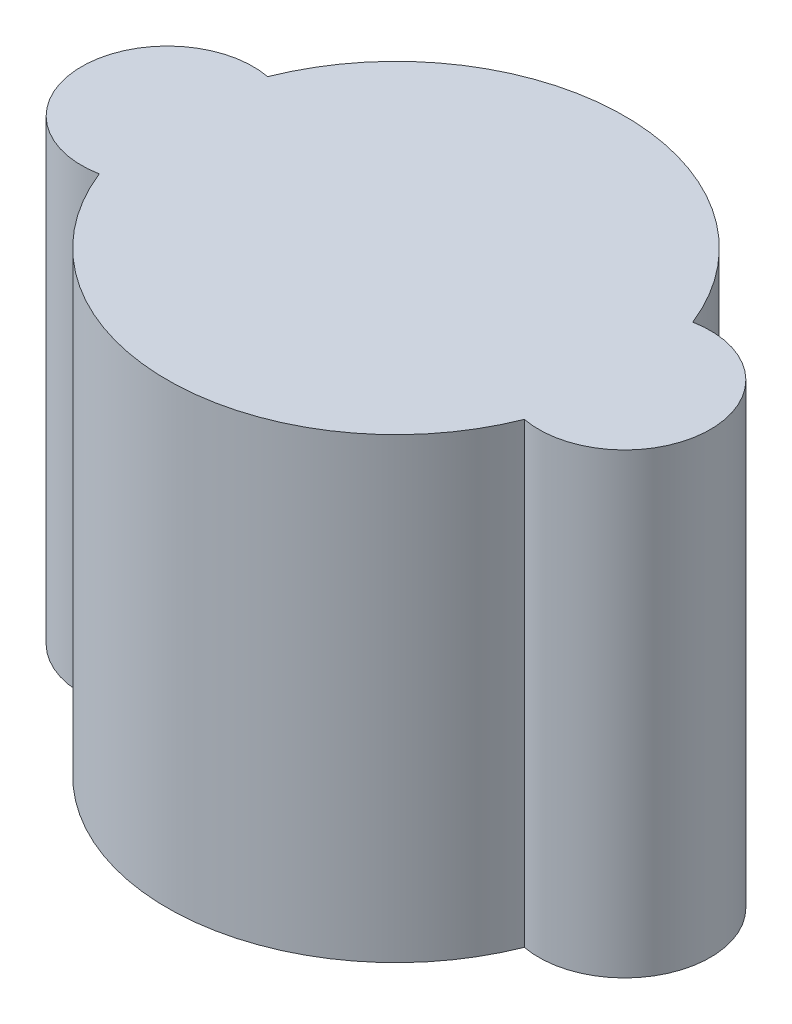
SolidWorks part; units mm, degrees
ref_plane "Front Plane" through (0, 0, 0) normal (0, 0, 1) x (1, 0, 0)
ref_plane "Top Plane" through (0, 0, 0) normal (0, 1, 0) x (1, 0, 0)
ref_plane "Right Plane" through (0, 0, 0) normal (1, 0, 0) x (0, 0, -1)
sketch "Sketch2" plane through (0, 0, 0) normal (0, 1, 0) x (1, 0, 0)
  circle A0 centre (0, 0) radius 8
  circle A1 centre (8, 0) radius 3
  circle A2 centre (-8, 0) radius 3
  dimension "D1" = 6
  dimension "D2" = 6
  dimension "D3" = 16
extrude "Boss-Extrude1" add sketch "Sketch2" along normal blind 16 contours A2 A0 A1 | A0 A1 | A0 A1
